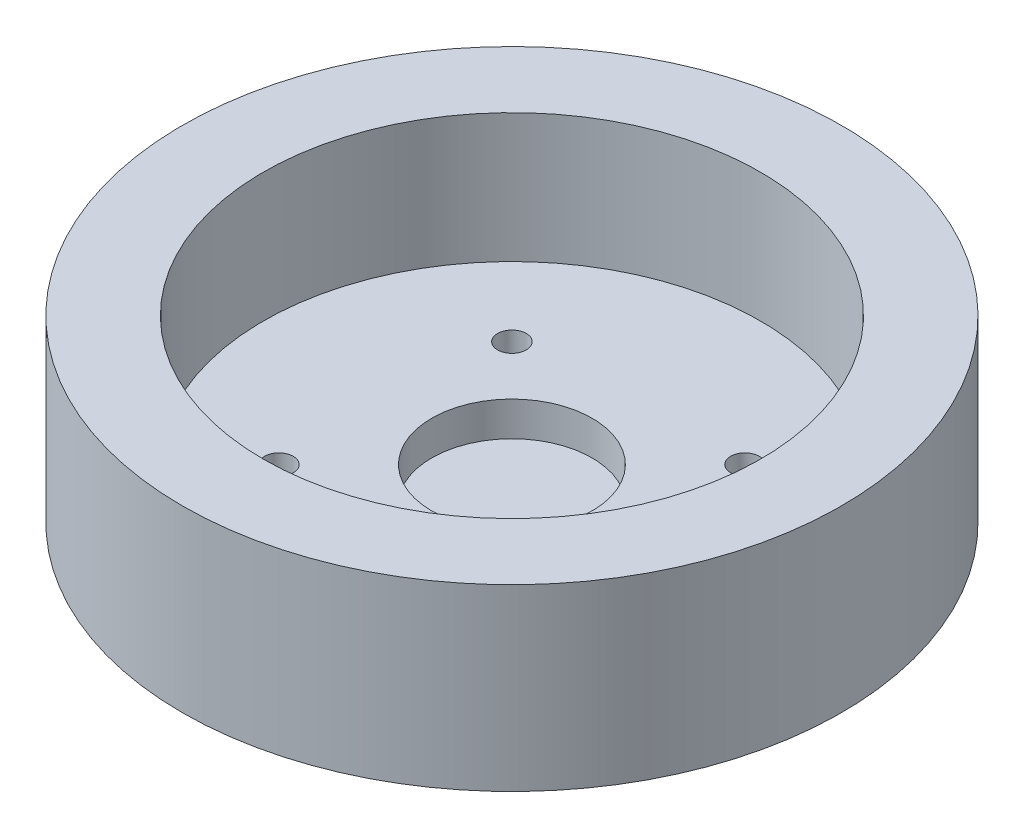
SolidWorks part; units mm, degrees
ref_plane "前视基准面" through (0, 0, 0) normal (0, 0, 1) x (1, 0, 0)
ref_plane "上视基准面" through (0, 0, 0) normal (0, 1, 0) x (1, 0, 0)
ref_plane "右视基准面" through (0, 0, 0) normal (1, 0, 0) x (0, 0, -1)
sketch "草图1" plane through (0, 0, 0) normal (0, 1, 0) x (1, 0, 0)
  circle A0 centre (0, 0) radius 16.35
  circle A1 centre (0, 0) radius 5.6
  circle A2 centre (0, 0) radius 15 construction
  circle A3 centre (0, 0) radius 23
  circle A4 centre (0, 0) radius 17.35
  dimension "D1" = 32.7
  dimension "D2" = 11.2
  dimension "D3" = 30
  dimension "D4" = 46
  dimension "D5" = 34.7
extrude "凸台-拉伸1" add sketch "草图1" along normal blind 3.5 contours A1 | A4
sketch "草图3" plane through (0, 0, 0) normal (0, 1, 0) x (1, 0, 0)
  circle A0 centre (0, 0) radius 23 construction
  circle A1 centre (0, 0) radius 23
  circle A2 centre (0, 0) radius 17.35 construction
  circle A3 centre (0, 0) radius 17.35
extrude "凸台-拉伸3" add sketch "草图3" along normal blind 12.5
sketch "草图4" plane through (0, 0, 0) normal (0, 1, 0) x (1, 0, 0)
  circle A0 centre (0, 0) radius 5.6 construction
  circle A1 centre (0, 0) radius 5.6
extrude "凸台-拉伸4" add sketch "草图4" along normal blind 1.1
sketch "草图6" plane through (0, 0, 0) normal (0, 1, 0) x (1, 0, 0)
  line L0 (-23.1107, 23.1107) -> (0, 0) construction
  line L1 (0, 0) -> (22.5537, 22.5537) construction
  circle A0 centre (0, 0) radius 16.35 construction
  circle A1 centre (0, 0) radius 16.35 construction
  circle A2 centre (0, 0) radius 17.35 construction
  circle A3 centre (0, 0) radius 17.35 construction
  circle A4 centre (8.1317, 8.1317) radius 1
  circle A5 centre (7.4246, -7.4246) radius 1
  circle A6 centre (-8.1317, -8.1317) radius 1
  circle A7 centre (-7.4246, 7.4246) radius 1
  circle A8 centre (0, 0) radius 5.6 construction
  circle A9 centre (0, 0) radius 5.6 construction
  dimension "D1" = 32.7
  dimension "D2" = 34.7
  dimension "D3" = 2
  dimension "D4" = 2
  dimension "D5" = 2
  dimension "D6" = 2
  dimension "D7" = 11.2
  dimension "D8" = 10.5
  dimension "D9" = 10.5
  dimension "D10" = 11.5
  dimension "D11" = 11.5
extrude "切除-拉伸3" cut sketch "草图6" against normal mid plane 10
sketch "草图8" plane through (0, 0, 0) normal (0, -1, 0) x (1, 0, 0)
  circle A0 centre (-8.1317, 8.1317) radius 1 construction
  circle A1 centre (-8.1317, 8.1317) radius 1 construction
  circle A2 centre (-8.1317, 8.1317) radius 1.91
  circle A3 centre (7.4246, 7.4246) radius 1.91
  circle A4 centre (-7.4246, -7.4246) radius 1.91
  circle A5 centre (8.1317, -8.1317) radius 1.91
  dimension "D1" = 3.82
  dimension "D2" = 3.82
  dimension "D3" = 3.82
  dimension "D4" = 3.82
extrude "切除-拉伸4" cut sketch "草图8" against normal blind 1.9
